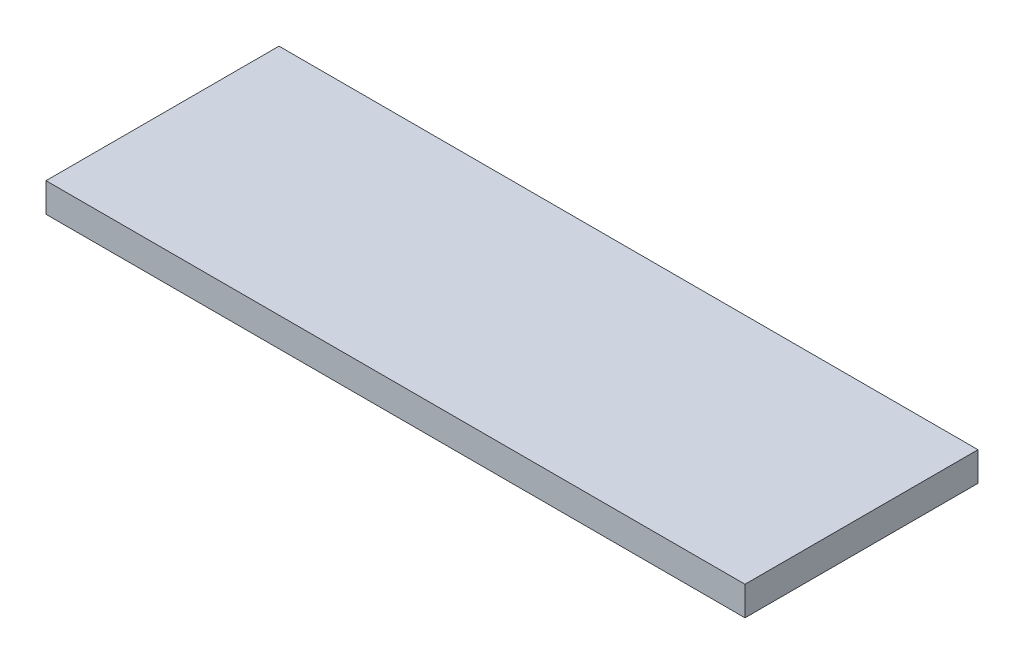
SolidWorks part; units mm, degrees
material "Miedź"
ref_plane "Front Plane" through (0, 0, 0) normal (0, 0, 1) x (1, 0, 0)
ref_plane "Top Plane" through (0, 0, 0) normal (0, 1, 0) x (1, 0, 0)
ref_plane "Right Plane" through (0, 0, 0) normal (1, 0, 0) x (0, 0, -1)
sketch "Szkic1" plane through (0, 0, 0) normal (0, 1, 0) x (1, 0, 0)
  line L1 (-3.0221, -1.0001) -> (2.9779, -1.0001)
  line L2 (-3.0221, -1.0001) -> (-3.0221, 0.9999)
  line L3 (-3.0221, 0.9999) -> (2.9779, 0.9999)
  line L4 (2.9779, -1.0001) -> (2.9779, 0.9999)
extrude "Dodanie-wyciągnięcie1" add sketch "Szkic1" along normal blind 0.25 contours L1 L4 L3 L2
